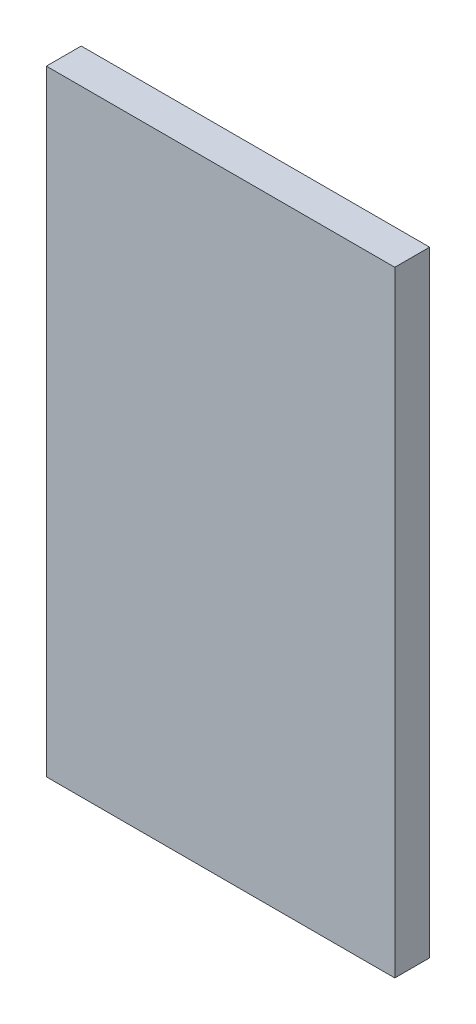
SolidWorks part; units mm, degrees
ref_plane "Front Plane" through (0, 0, 0) normal (0, 0, 1) x (1, 0, 0)
ref_plane "Top Plane" through (0, 0, 0) normal (0, 1, 0) x (1, 0, 0)
ref_plane "Right Plane" through (0, 0, 0) normal (1, 0, 0) x (0, 0, -1)
sketch "Sketch1" plane through (0, 0, 0) normal (0, 0, 1) x (1, 0, 0)
  line L1 (-150, -265) -> (150, -265)
  line L2 (-150, -265) -> (-150, 265)
  line L3 (-150, 265) -> (150, 265)
  line L4 (150, -265) -> (150, 265)
  line L5 (-150, -265) -> (150, 265) construction
  line L6 (-150, 265) -> (150, -265) construction
  point P0 (0, 0)
  dimension "D1" = 530
  dimension "D2" = 300
extrude "Boss-Extrude1" add sketch "Sketch1" along normal blind 30
sketch "Sketch2" plane through (0, 0, 30) normal (0, 0, 1) x (1, 0, 0)
  line L0 (150, 265) -> (-150, 265) construction
  line L1 (-110, 225) -> (110, 225)
  line L2 (-110, 225) -> (-110, -225)
  line L3 (-110, -225) -> (110, -225)
  line L4 (110, 225) -> (110, -225)
  line L5 (-150, -265) -> (150, -265) construction
  line L6 (-150, 265) -> (-150, -265) construction
  line L7 (150, -265) -> (150, 265) construction
  dimension "D1" = 40
  dimension "D2" = 40
  dimension "D3" = 40
  dimension "D4" = 40
